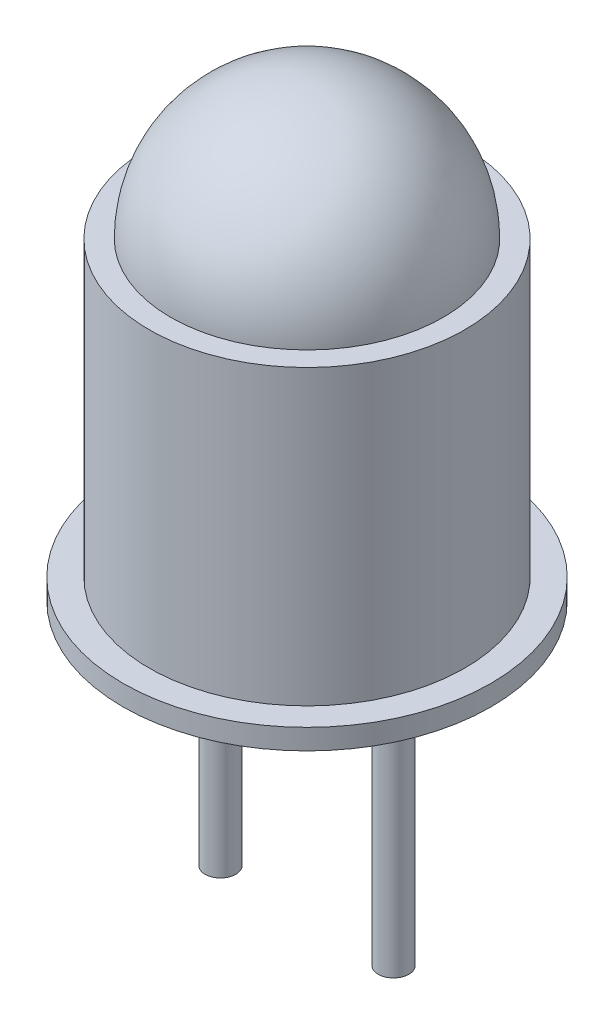
SolidWorks part; units mm, degrees
ref_plane "前视基准面" through (0, 0, 0) normal (0, 0, 1) x (1, 0, 0)
ref_plane "上视基准面" through (0, 0, 0) normal (0, 1, 0) x (1, 0, 0)
ref_plane "右视基准面" through (0, 0, 0) normal (1, 0, 0) x (0, 0, -1)
sketch "草图1" plane through (0, 0, 0) normal (0, 1, 0) x (1, 0, 0)
  circle A0 centre (0, 0) radius 2.315
extrude "凸台-拉伸1" add sketch "草图1" along normal blind 4.3
sketch "草图2" plane through (0, 0, 0) normal (0, 0, 1) x (1, 0, 0)
  line L0 (2.315, 4.3) -> (-2.315, 4.3) construction
  line L1 (-2, 4.3) -> (0, 4.3)
  line L2 (0, 11.523) -> (0, -4.7558) construction
  line L3 (0, 4.3) -> (0, 6.3)
  arc A0 (-2, 4.3) -> (0, 6.3) centre (0, 4.3) cw
revolve "旋转2" add sketch "草图2" angle 360 about L2
sketch "草图3" plane through (0, 0, 0) normal (0, -1, 0) x (1, 0, 0)
  circle A0 centre (0, 0) radius 2.7
extrude "凸台-拉伸2" add sketch "草图3" along normal blind 0.3
sketch "草图4" plane through (0, -0.3, 0) normal (0, -1, 0) x (1, 0, 0)
  circle A0 centre (0, 0) radius 1.27
sketch "草图5" plane through (0, -0.3, 0) normal (0, -1, 0) x (1, 0, 0)
  circle A0 centre (-1.27, 0) radius 0.225
  circle A1 centre (0, 0) radius 1.27 construction
  circle A2 centre (1.27, 0) radius 0.225
  circle A3 centre (0, -1.27) radius 0.225
extrude "凸台-拉伸3" add sketch "草图5" along normal blind 4
